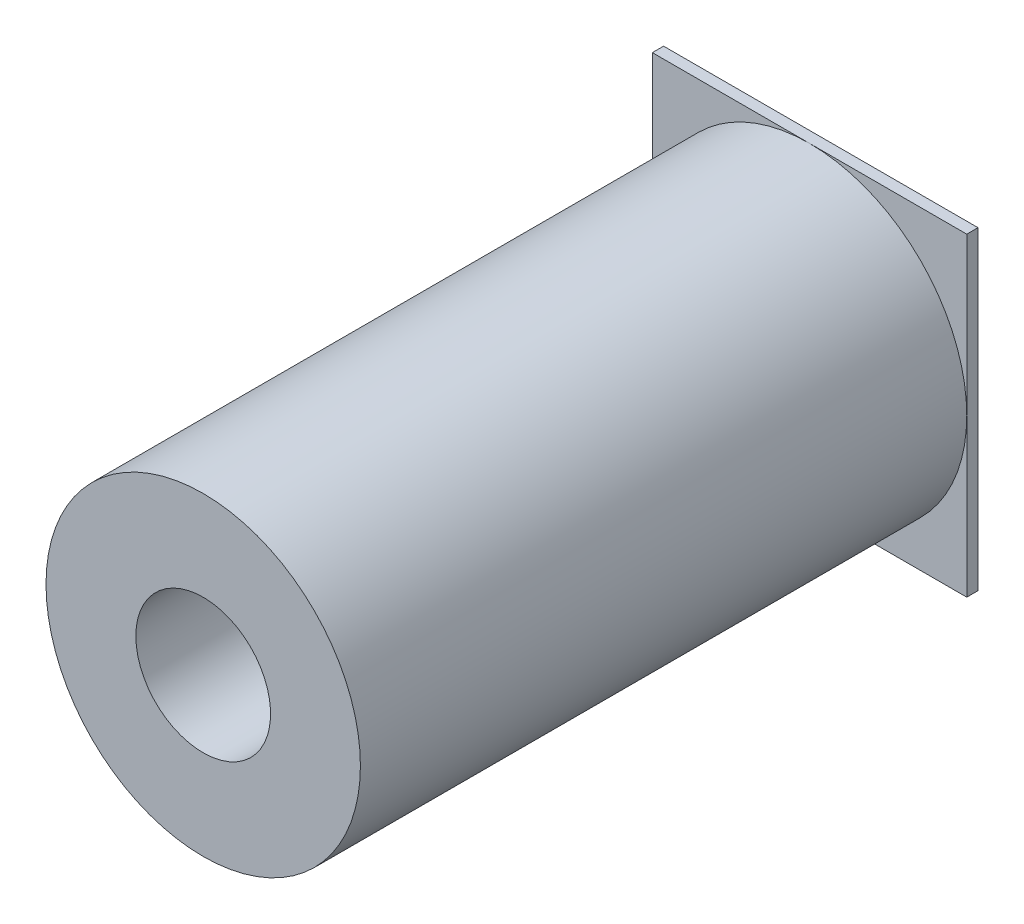
SolidWorks part; units mm, degrees
ref_plane "Front Plane" through (0, 0, 0) normal (0, 0, 1) x (1, 0, 0)
ref_plane "Top Plane" through (0, 0, 0) normal (0, 1, 0) x (1, 0, 0)
ref_plane "Right Plane" through (0, 0, 0) normal (1, 0, 0) x (0, 0, -1)
sketch "Sketch1" plane through (0, 0, 0) normal (0, 0, 1) x (1, 0, 0)
  line L1 (-14, 14) -> (14, 14)
  line L2 (-14, 14) -> (-14, -14)
  line L3 (-14, -14) -> (14, -14)
  line L4 (14, 14) -> (14, -14)
  line L5 (-14, 14) -> (14, -14) construction
  line L6 (-14, -14) -> (14, 14) construction
  point P0 (0, 0)
  dimension "D1" = 28
  dimension "D2" = 28
extrude "Boss-Extrude1" add sketch "Sketch1" along normal blind 1
sketch "Sketch2" plane through (0, 0, 1) normal (0, 0, 1) x (1, 0, 0)
  circle A0 centre (0, 0) radius 14
  dimension "D1" = 28
extrude "Boss-Extrude2" add sketch "Sketch2" along normal blind 54
sketch "Sketch3" plane through (0, 0, 0) normal (0, 0, -1) x (-1, 0, 0)
  circle A0 centre (0, 0) radius 6
  dimension "D1" = 12
extrude "Cut-Extrude1" cut sketch "Sketch3" against normal through all
